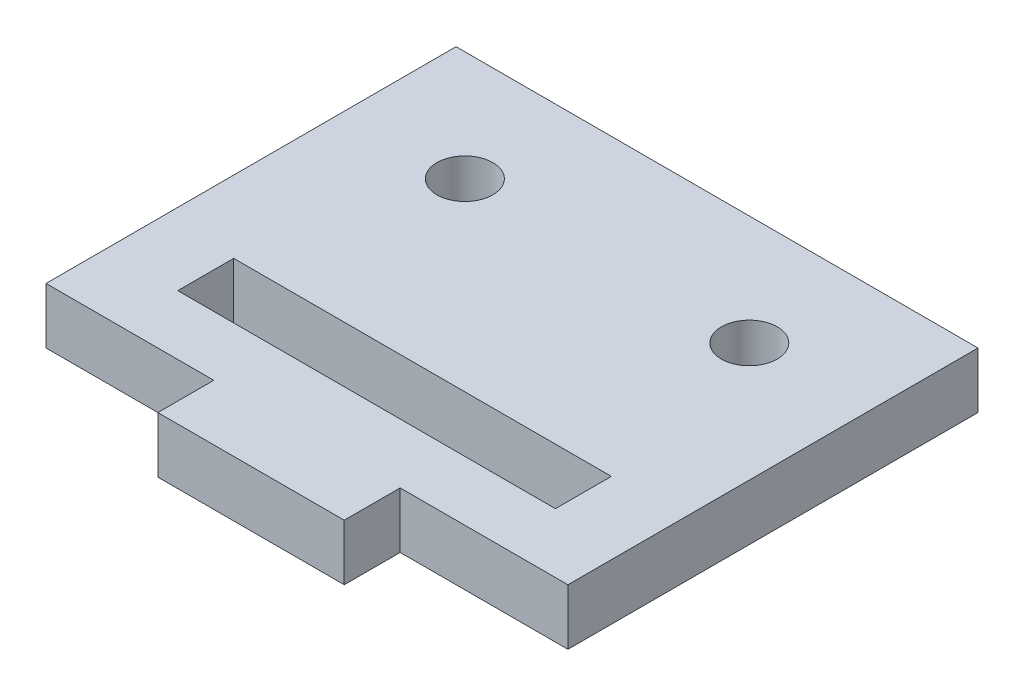
SolidWorks part; units mm, degrees
ref_plane "Front Plane" through (0, 0, 0) normal (0, 0, 1) x (1, 0, 0)
ref_plane "Top Plane" through (0, 0, 0) normal (0, 1, 0) x (1, 0, 0)
ref_plane "Right Plane" through (0, 0, 0) normal (1, 0, 0) x (0, 0, -1)
sketch "Sketch1" plane through (0, 0, 0) normal (0, 1, 0) x (1, 0, 0)
  line L0 (-5, 0) -> (5, 0)
  line L1 (5, 0) -> (5, 3)
  line L2 (5, 3) -> (14, 3)
  line L3 (14, 3) -> (14, 25)
  line L4 (14, 25) -> (-14, 25)
  line L5 (10.13, 6.2) -> (10.13, 9.2)
  line L6 (10.13, 9.2) -> (-10.13, 9.2)
  line L8 (-10.13, 6.2) -> (10.13, 6.2)
  line L9 (0, 25) -> (0, 9.2) construction
  line L10 (-10.13, 6.2) -> (-10.13, 9.2)
  line L11 (-14, 3) -> (-14, 25)
  line L12 (-5, 3) -> (-14, 3)
  line L13 (-5, 0) -> (-5, 3)
  line L14 (0, 6.2) -> (0, 0) construction
  circle A0 centre (7.63, 19.1) radius 1.5
  circle A1 centre (-7.63, 19.1) radius 1.5
  dimension "D9" = 3
  dimension "D1" = 3
  dimension "D2" = 5
  dimension "D3" = 9
  dimension "D4" = 6.37
  dimension "D5" = 5.9
  dimension "D6" = 22
  dimension "D7" = 3.2
  dimension "D8" = 3
  dimension "D10" = 20.26
extrude "Boss-Extrude1" add sketch "Sketch1" along normal blind 3
